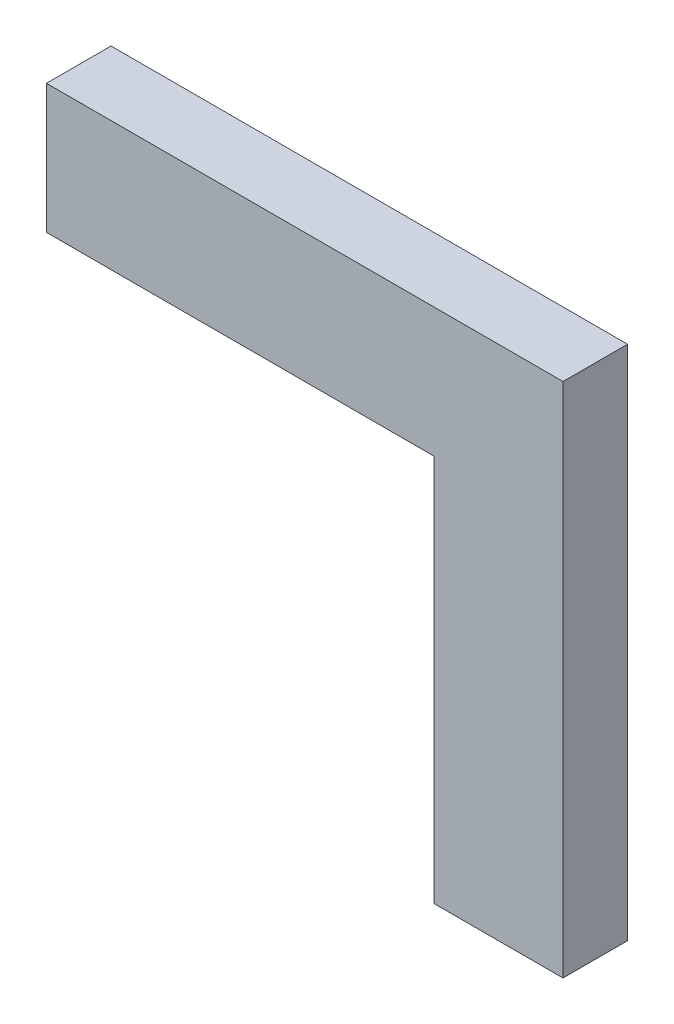
SolidWorks part; units mm, degrees
material "ABS"
ref_plane "Front Plane" through (0, 0, 0) normal (0, 0, 1) x (1, 0, 0)
ref_plane "Top Plane" through (0, 0, 0) normal (0, 1, 0) x (1, 0, 0)
ref_plane "Right Plane" through (0, 0, 0) normal (1, 0, 0) x (0, 0, -1)
sketch "Sketch3" plane through (0, 0, 0) normal (0, 0, 1) x (1, 0, 0)
  line L1 (-76.2, 25.4) -> (76.2, 25.4)
  line L2 (-76.2, 25.4) -> (-76.2, -25.4)
  line L3 (-76.2, -25.4) -> (76.2, -25.4)
  line L5 (-76.2, 25.4) -> (76.2, -25.4) construction
  line L6 (-76.2, -25.4) -> (76.2, 25.4) construction
  line L7 (76.2, 25.4) -> (127, 25.4)
  line L8 (76.2, -25.4) -> (76.2, -177.8)
  line L9 (76.2, -177.8) -> (127, -177.8)
  line L10 (127, 25.4) -> (127, -177.8)
  point P0 (0, 0)
  dimension "D1" = 50.8
  dimension "D2" = 152.4
  dimension "D3" = 203.2
  dimension "D4" = 50.8
  dimension "D5" = 50.8
extrude "Boss-Extrude1" add sketch "Sketch3" along normal blind 25.4 contours L3 L8 L9 L10 L7 L1 L2
